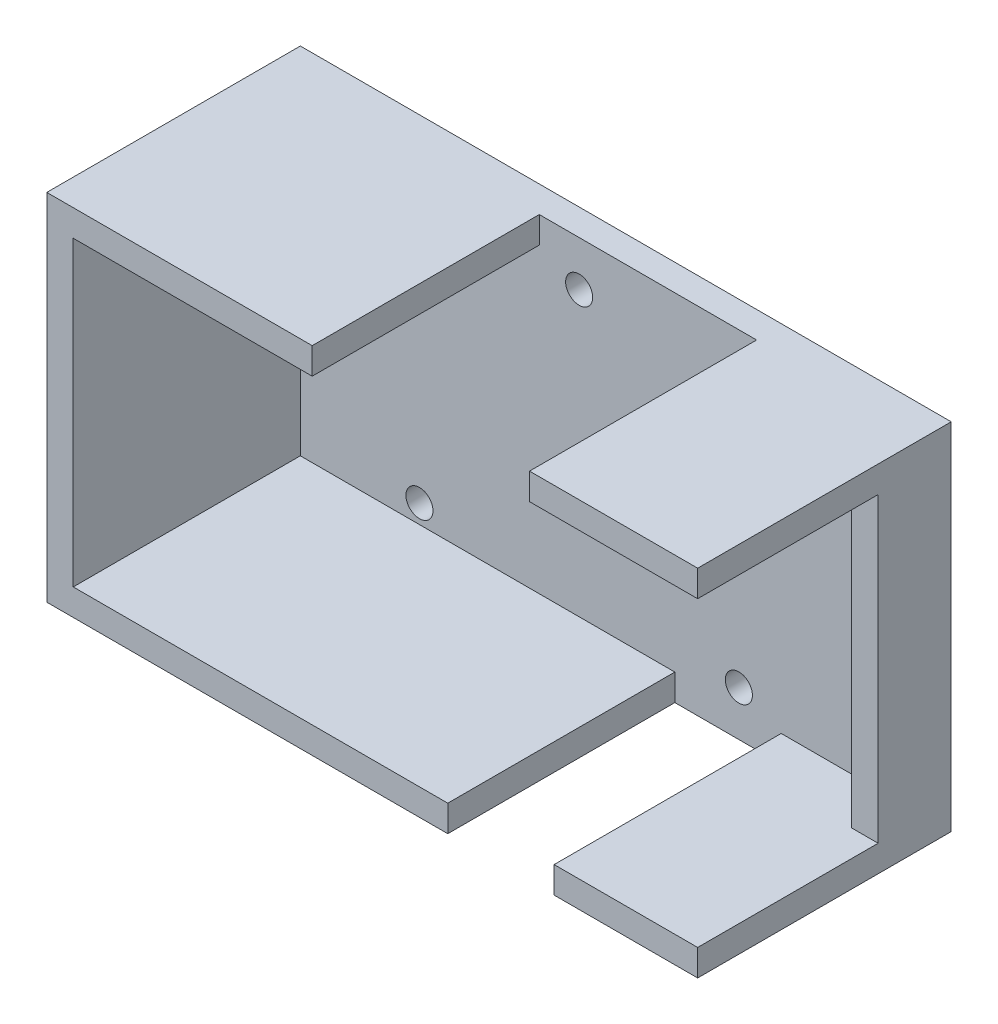
SolidWorks part; units mm, degrees
ref_plane "Front Plane" through (0, 0, 0) normal (0, 0, 1) x (1, 0, 0)
ref_plane "Top Plane" through (0, 0, 0) normal (0, 1, 0) x (1, 0, 0)
ref_plane "Right Plane" through (0, 0, 0) normal (1, 0, 0) x (0, 0, -1)
sketch "Sketch1" plane through (0, 0, 0) normal (0, 0, 1) x (1, 0, 0)
  line L1 (-27.4828, -14.986) -> (27.4828, -14.986)
  line L2 (-27.4828, -14.986) -> (-27.4828, 14.986)
  line L3 (-27.4828, 14.986) -> (27.4828, 14.986)
  line L4 (27.4828, -14.986) -> (27.4828, 14.986)
  line L5 (-27.4828, -14.986) -> (27.4828, 14.986) construction
  line L6 (-27.4828, 14.986) -> (27.4828, -14.986) construction
  point P0 (0, 0)
  dimension "D1" = 54.9656
  dimension "D2" = 29.972
extrude "Boss-Extrude1" add sketch "Sketch1" along normal blind 21.4122
shell "Shell1" thickness 2.2352
sketch "Sketch2" plane through (0, 0, 0) normal (0, 0, -1) x (-1, 0, 0)
  line L0 (27.4828, 11.176) -> (1.7018, 11.176) construction
  line L2 (27.4828, 14.986) -> (27.4828, -14.986) construction
  line L3 (27.4828, -11.176) -> (15.1892, -11.176) construction
  line L4 (15.1892, -11.176) -> (-11.7856, -11.176) construction
  line L5 (-27.4828, 14.986) -> (27.4828, 14.986) construction
  circle A0 centre (1.7018, 11.176) radius 1.143
  circle A1 centre (-11.7856, -11.176) radius 1.143
  circle A2 centre (15.1892, -11.176) radius 1.143
  dimension "D6" = 2.286
  dimension "D1" = 26.9748
  dimension "D2" = 13.4874
  dimension "D3" = 22.352
  dimension "D4" = 12.2936
  dimension "D5" = 3.81
extrude "Cut-Extrude1" cut sketch "Sketch2" against normal through all
sketch "Sketch3" plane through (0, 0, 21.4122) normal (0, 0, 1) x (1, 0, 0)
  line L0 (27.4828, -14.986) -> (27.4828, 14.986) construction
  line L1 (25.2476, -12.7508) -> (27.4828, -12.7508)
  line L2 (25.2476, -12.7508) -> (25.2476, 12.7508)
  line L3 (25.2476, 12.7508) -> (27.4828, 12.7508)
  line L4 (27.4828, -12.7508) -> (27.4828, 12.7508)
extrude "Cut-Extrude2" cut sketch "Sketch3" against normal blind 15.24
sketch "Sketch4" plane through (0, 0, 21.4122) normal (0, 0, 1) x (1, 0, 0)
  line L0 (-27.4828, -14.986) -> (27.4828, -14.986) construction
  line L1 (15.361, -14.986) -> (6.3795, -14.986)
  line L2 (15.361, -14.986) -> (15.361, -12.7508)
  line L3 (15.361, -12.7508) -> (6.3795, -12.7508)
  line L4 (6.3795, -14.986) -> (6.3795, -12.7508)
  line L5 (-25.2476, -12.7508) -> (27.4828, -12.7508) construction
  line L6 (27.4828, 14.986) -> (-27.4828, 14.986) construction
  line L7 (-5.0683, 14.986) -> (13.284, 14.986)
  line L8 (-5.0683, 14.986) -> (-5.0683, 12.7508)
  line L9 (-5.0683, 12.7508) -> (13.284, 12.7508)
  line L10 (13.284, 14.986) -> (13.284, 12.7508)
  line L11 (27.4828, 12.7508) -> (-25.2476, 12.7508) construction
extrude "Cut-Extrude3" cut sketch "Sketch4" against normal up to surface (19.177 mm away) up to face at (-16.3322, -11.176, 2.2352)
sketch "Sketch6" plane through (-27.4828, 0, 0) normal (-1, 0, 0) x (0, 0, 1)
  line L0 (0, 14.986) -> (0, -14.986) construction
  line L1 (0, 7.366) -> (0.635, 7.366)
  line L2 (0, 7.366) -> (0, 5.5372)
  line L3 (0, 5.5372) -> (0.635, 5.5372)
  line L4 (0.635, 7.366) -> (0.635, 5.5372)
  line L5 (21.4122, 14.986) -> (0, 14.986) construction
  line L6 (0, -5.3848) -> (0.635, -5.3848)
  line L7 (0, -5.3848) -> (0, -7.2136)
  line L8 (0, -7.2136) -> (0.635, -7.2136)
  line L9 (0.635, -5.3848) -> (0.635, -7.2136)
  dimension "D1" = 1.8288
  dimension "D2" = 0.635
  dimension "D3" = 10.922
  dimension "D4" = 7.62
extrude "Boss-Extrude2" add sketch "Sketch6" along normal blind 5.08
